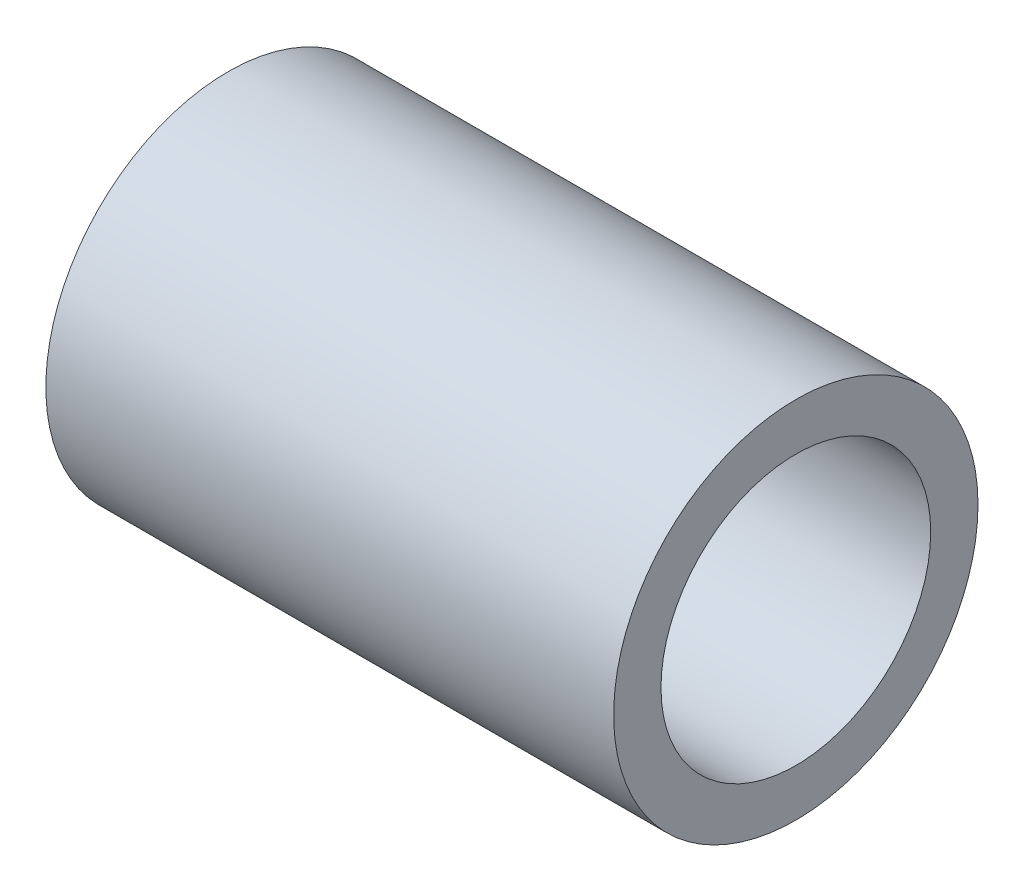
SolidWorks part; units mm, degrees
ref_plane "Front Plane" through (0, 0, 0) normal (0, 0, 1) x (1, 0, 0)
ref_plane "Top Plane" through (0, 0, 0) normal (0, 1, 0) x (1, 0, 0)
ref_plane "Right Plane" through (0, 0, 0) normal (1, 0, 0) x (0, 0, -1)
sketch "Sketch1" plane through (0, 0, 0) normal (1, 0, 0) x (0, 0, -1)
  circle A0 centre (0, 0) radius 8.55
  circle A1 centre (0, 0) radius 11.55
  dimension "D1" = 17.1
  dimension "D2" = 3
extrude "Boss-Extrude1" add sketch "Sketch1" along normal blind 12
sketch "Sketch2" plane through (12, 0, 0) normal (1, 0, 0) x (0, 0, -1)
  line L0 (-3.65, 7.7318) -> (-3.65, -7.7318)
  line L1 (3.65, 7.7318) -> (3.65, -7.7318)
  arc A1 (3.65, 7.7318) -> (-3.65, 7.7318) centre (0, 0) ccw
  circle A2 centre (0, 0) radius 11.55
  circle A3 centre (0, 0) radius 11.55 construction
  circle A4 centre (0, 0) radius 8.55 construction
  arc A5 (-3.65, -7.7318) -> (3.65, -7.7318) centre (0, 0) ccw
  circle A6 centre (0, 0) radius 8.55
  dimension "D1" = 7.3
  dimension "D2" = 3.65
extrude "Boss-Extrude2" add sketch "Sketch2" along normal blind 4 separate body contours L1 A5 L0 A1
sketch "Sketch3" plane through (12, 0, 0) normal (1, 0, 0) x (0, 0, -1)
  circle A0 centre (0, 0) radius 8.55
  circle A1 centre (0, 0) radius 11.55
extrude "Boss-Extrude3" add sketch "Sketch3" along normal blind 4
sketch "Sketch4" plane through (16, 0, 0) normal (1, 0, 0) x (0, 0, -1)
  circle A0 centre (0, 0) radius 8.55
  circle A1 centre (0, 0) radius 11.55
extrude "Boss-Extrude4" add sketch "Sketch4" along normal blind 20
